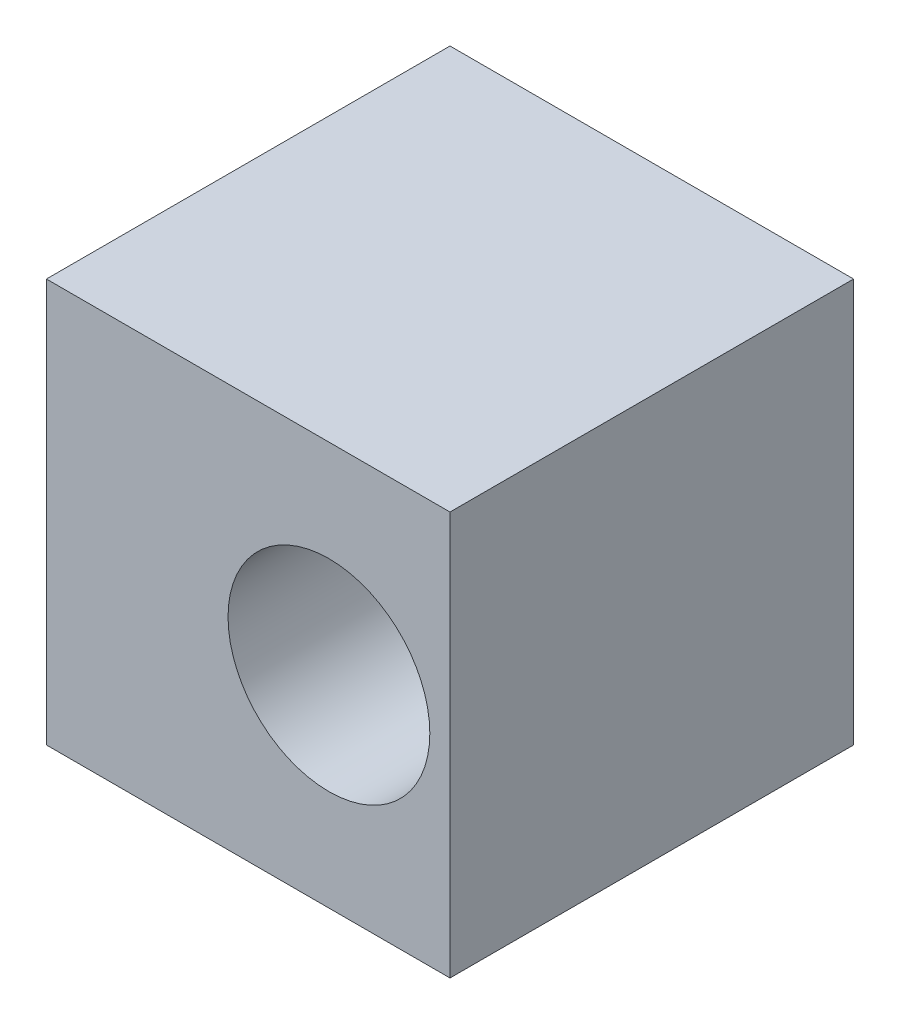
SolidWorks part; units mm, degrees
ref_plane "Front Plane" through (0, 0, 0) normal (0, 0, 1) x (1, 0, 0)
ref_plane "Top Plane" through (0, 0, 0) normal (0, 1, 0) x (1, 0, 0)
ref_plane "Right Plane" through (0, 0, 0) normal (1, 0, 0) x (0, 0, -1)
sketch "Sketch1" plane through (0, 0, 0) normal (0, 0, 1) x (1, 0, 0)
  line L1 (0, 0) -> (10, 0)
  line L2 (0, 0) -> (0, 10)
  line L3 (0, 10) -> (10, 10)
  line L4 (10, 0) -> (10, 10)
extrude "Boss-Extrude1" add sketch "Sketch1" along normal blind 10
sketch "Sketch2" plane through (0, 0, 10) normal (0, 0, 1) x (1, 0, 0)
  circle A0 centre (7, 5) radius 2.5
extrude "Cut-Extrude1" cut sketch "Sketch2" against normal through all
